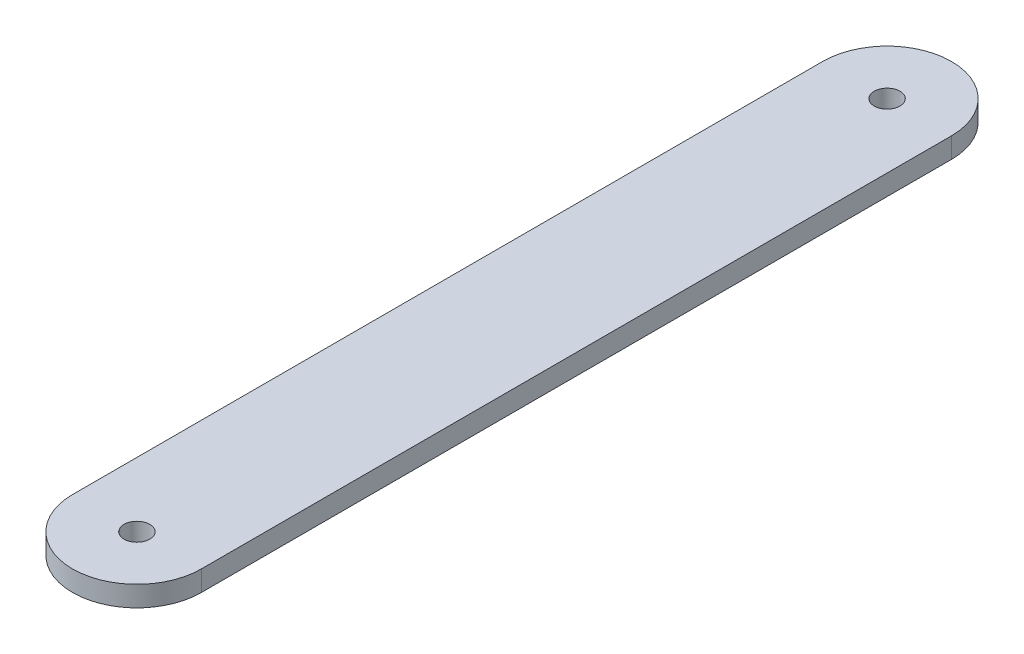
SolidWorks part; units mm, degrees
ref_plane "Front Plane" through (0, 0, 0) normal (0, 0, 1) x (1, 0, 0)
ref_plane "Top Plane" through (0, 0, 0) normal (0, 1, 0) x (1, 0, 0)
ref_plane "Right Plane" through (0, 0, 0) normal (1, 0, 0) x (0, 0, -1)
sketch "Sketch2" plane through (0, 0, 0) normal (0, 1, 0) x (1, 0, 0)
  line L0 (-5, 58.2405) -> (-5, 0)
  line L1 (5, 58.2405) -> (5, 0)
  circle A0 centre (0, 0) radius 1
  circle A1 centre (0, 58.2405) radius 1
  arc A2 (5, 0) -> (-5, 0) centre (0, 0) cw
  arc A3 (5, 58.2405) -> (-5, 58.2405) centre (0, 58.2405) ccw
  dimension "D2" = 2
  dimension "D3" = 5
  dimension "D1" = 58.2405
extrude "Boss-Extrude1" add sketch "Sketch2" along normal blind 1.5875
